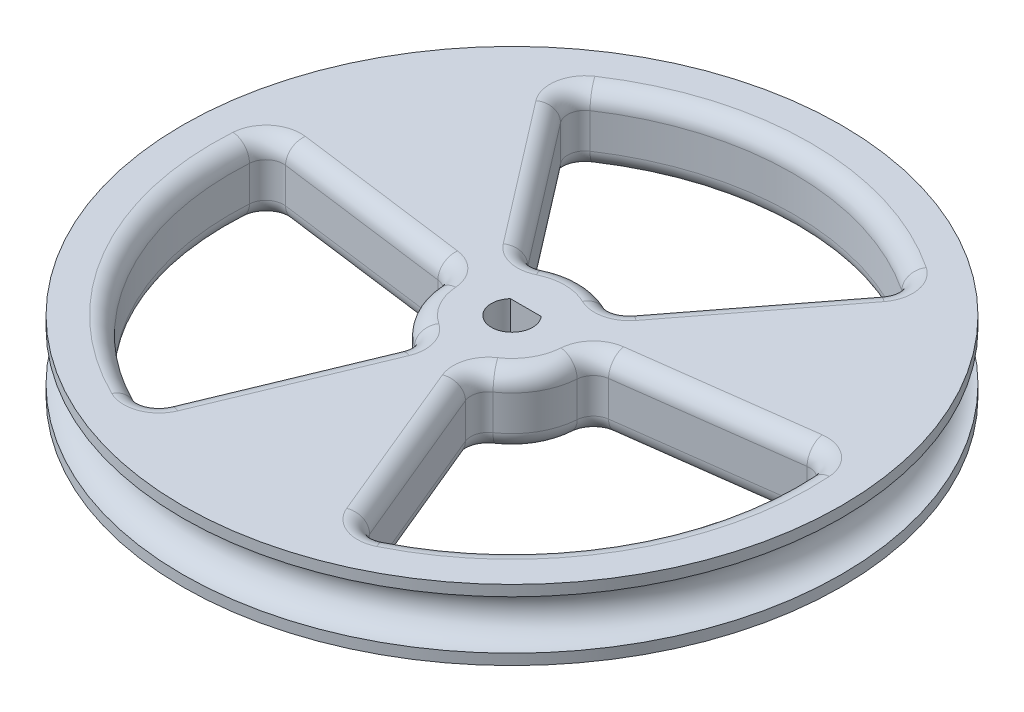
SolidWorks part; units mm, degrees
ref_plane "Front Plane" through (0, 0, 0) normal (0, 0, 1) x (1, 0, 0)
ref_plane "Top Plane" through (0, 0, 0) normal (0, 1, 0) x (1, 0, 0)
ref_plane "Right Plane" through (0, 0, 0) normal (1, 0, 0) x (0, 0, -1)
sketch "Sketch1" plane through (0, 0, 0) normal (0, 1, 0) x (1, 0, 0)
  line L0 (0, 25.5524) -> (0, 22.0218) construction
  circle A0 centre (0, 0) radius 25.5524 construction
  circle A1 centre (0, 0) radius 22.0218 construction
  circle A2 centre (0, 0) radius 23.8156
  circle A3 centre (0, 23.8156) radius 1.7938 construction
  circle A4 centre (0, 0) radius 6.35 construction
  point P34 (0, 0)
  dimension "D1" = 51.1048
  dimension "D2" = 44.0436
extrude "Boss-Extrude1" add sketch "Sketch1" along normal blind 5.08 contours A2
sketch "Sketch2" plane through (0, 5.08, 0) normal (0, 1, 0) x (1, 0, 0)
  line L0 (0, 1.4922) -> (0, -1.4922) construction
  line L1 (-1.1146, 0.9922) -> (1.1146, 0.9922) construction
  line L2 (-1.1146, 0.9922) -> (1.1146, 0.9922)
  arc A0 (-1.1146, 0.9922) -> (1.1146, 0.9922) centre (0, 0) ccw construction
  arc A1 (-1.1146, 0.9922) -> (1.1146, 0.9922) centre (0, 0) ccw
  dimension "D1" = 2.9845
  dimension "D2" = 0.5
extrude "Cut-Extrude1" cut sketch "Sketch2" against normal blind 5.08
sketch "Sketch5" plane through (0, 0, 0) normal (0, 0, 1) x (1, 0, 0)
  line L0 (0, 0) -> (-1.1146, 0)
  line L1 (0, 0) -> (-23.8156, 0) construction
  line L3 (0, 0) -> (-0.2993, -0.2058)
  line L4 (-23.8156, 5.08) -> (-23.8156, 0) construction
  line L7 (-23.8156, 0) -> (-23.8156, 5.08) construction
  line L8 (0, 4.3287) -> (0, 0) construction
  line L9 (-23.8156, 4.3053) -> (-23.8156, 0.7747)
  arc A0 (-23.8156, 0.7747) -> (-23.8156, 4.3053) centre (-23.8156, 2.54) ccw
revolve "Cut-Revolve2" cut sketch "Sketch5" angle 360 about L8
sketch "Sketch8" plane through (0, 5.08, 0) normal (0, 1, 0) x (1, 0, 0)
  line L0 (0, 0) -> (0, 0.9922)
  line L1 (1.1146, 0.9922) -> (-1.1146, 0.9922) construction
  line L2 (0, 0) -> (0, 20.32) construction
  line L3 (0, 0) -> (0, 0.9922)
  line L4 (0, 0) -> (12.37, 16.1209) construction
  line L5 (0, 0) -> (-12.37, 16.1209) construction
  line L6 (3.0925, 4.0302) -> (12.37, 16.1209)
  line L7 (0, 0.9922) -> (0, 0) construction
  line L8 (-12.37, 16.1209) -> (-3.0925, 4.0302)
  circle A0 centre (0, 0) radius 20.32 construction
  circle A1 centre (0, 0) radius 5.08 construction
  arc A2 (-12.37, 16.1209) -> (12.37, 16.1209) centre (0, 0) cw
  arc A3 (-3.0925, 4.0302) -> (3.0925, 4.0302) centre (0, 0) cw
  circle A4 centre (0, 0) radius 23.8156 construction
  dimension "D2" = 37.5
  dimension "D3" = 10.16
  dimension "D4" = 40.64
  dimension "D1" = 75
extrude "Cut-Extrude3" cut sketch "Sketch8" along direction (0, 1, 0) on the side against the normal through all contours L8 A3 L6 A2
fillet "Fillet22" radius 1.27 12 edges at (7.7313, 0, -10.0756) (7.7313, 5.08, -10.0756) (-7.7313, 0, -10.0756) (-7.7313, 5.08, -10.0756) (-3.0925, 2.54, -4.0302) (0, 0, -5.08) (3.0925, 2.54, -4.0302) (0, 5.08, -5.08) (12.37, 2.54, -16.1209) (0, 0, -20.32) (-12.37, 2.54, -16.1209) (0, 5.08, -20.32)
pattern_circular "CirPattern1" count 3 over 360 about axis through (0, 5.08, 0) along (0, 1, 0) of "Cut-Extrude3", "Fillet22"
